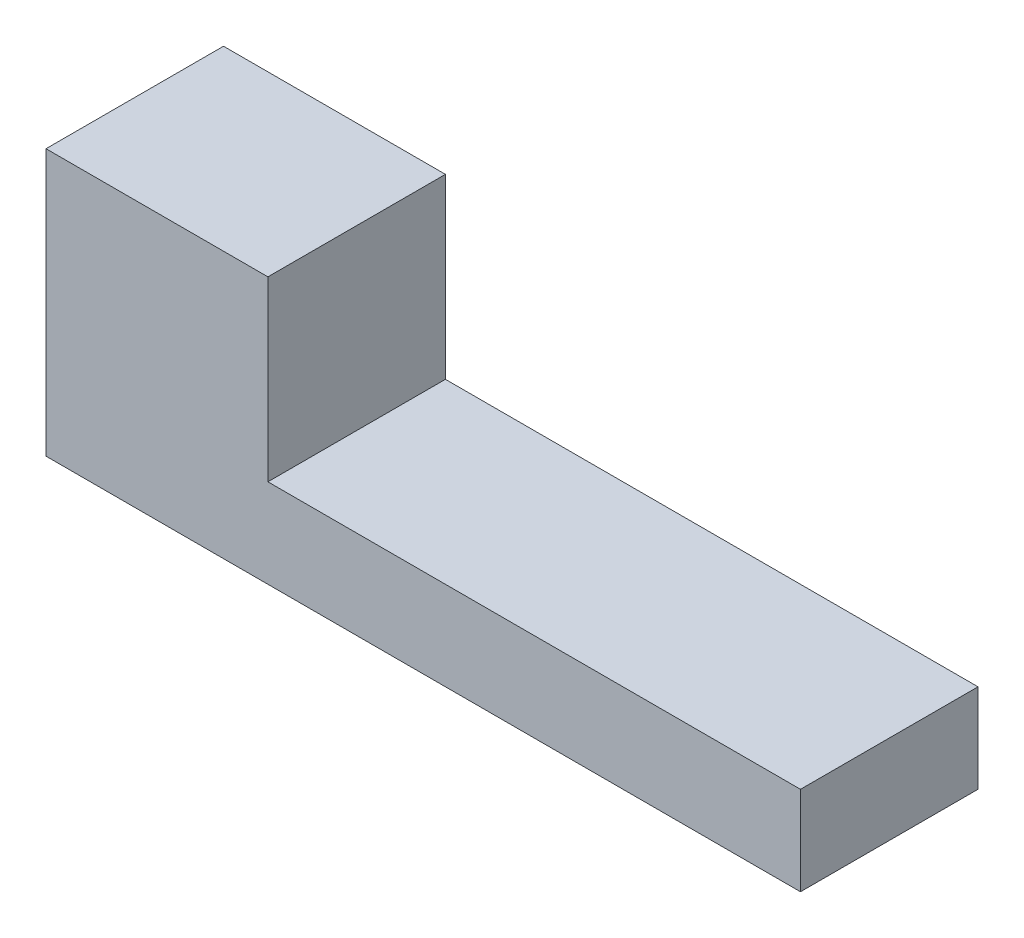
SolidWorks part; units mm, degrees
ref_plane "Front Plane" through (0, 0, 0) normal (0, 0, 1) x (1, 0, 0)
ref_plane "Top Plane" through (0, 0, 0) normal (0, 1, 0) x (1, 0, 0)
ref_plane "Right Plane" through (0, 0, 0) normal (1, 0, 0) x (0, 0, -1)
sketch "Sketch1" plane through (0, 0, 0) normal (0, 1, 0) x (1, 0, 0)
  line L1 (0, 0) -> (850, 0)
  line L2 (0, 0) -> (0, 200)
  line L3 (0, 200) -> (850, 200)
  line L4 (850, 0) -> (850, 200)
  dimension "D1" = 850
  dimension "D2" = 200
extrude "Boss-Extrude1" add sketch "Sketch1" along normal blind 100
sketch "Sketch2" plane through (0, 100, 0) normal (0, 1, 0) x (1, 0, 0)
  line L0 (850, 200) -> (0, 200) construction
  line L1 (0, 0) -> (250, 0)
  line L2 (0, 0) -> (0, 200)
  line L3 (0, 200) -> (250, 200)
  line L4 (250, 0) -> (250, 200)
  dimension "D1" = 250
extrude "Boss-Extrude2" add sketch "Sketch2" along normal blind 200
